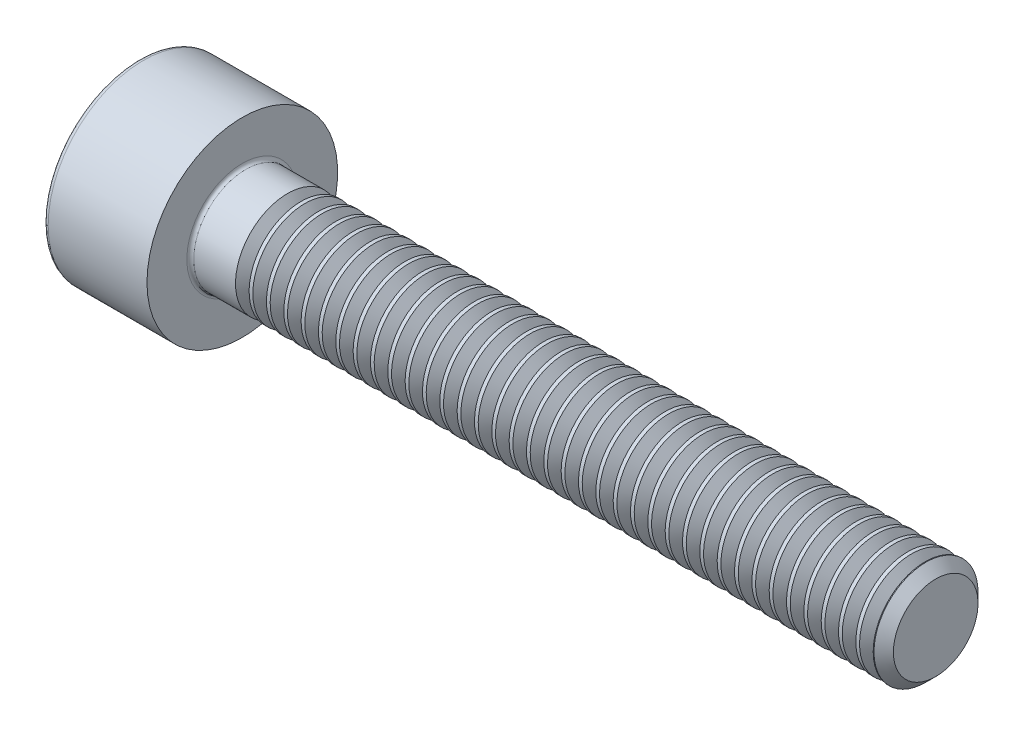
SolidWorks part; units mm, degrees
revolve "Base-Revolve" add sketch "BodySke"
sketch "BodySke" plane through (0, 0, 0) normal (0, 0, 1) x (1, 0, 0)
  line L0 (0, 0) -> (0, 2.75)
  line L1 (0, 2.75) -> (3, 2.75)
  line L2 (3, 2.75) -> (3, 1.5)
  line L3 (3, 1.5) -> (22.7195, 1.5)
  line L4 (23, 1.2195) -> (23, 0)
  line L5 (23, 0) -> (0, 0)
  line L6 (-31.75, 0) -> (127, 0) construction
  line L8 (23, 1.2195) -> (22.7195, 1.5)
  line L10 (23, -1.2195) -> (22.7195, -1.5) construction
  line L11 (3.5, 9.525) -> (3.5, 3.175) construction
  line L12 (3, 9.525) -> (3, 3.175) construction
  line L13 (-37, 9.525) -> (-37, 3.175) construction
  dimension "Head_ht" = 3
  dimension "Length" = 20
  dimension "Body_ch_ang" = 45
  dimension "Diameter" = 3
  dimension "Minor_dia" = 2.439
  dimension "Advance" = 0.5
  dimension "Thread_nom" = 20
  dimension "Thread_length" = 60
  dimension "Head_dia" = 5.5
cosmetic thread "ThreadCosmetic" [suppressed]
fillet "Fillet1" radius 0.1 1 edges at (3, 0, 1.5)
fillet "Fillet2" radius 0.15 1 edges at (0, 0, 2.75)
ref_plane "Plane1" through (0, 0, 0) normal (0, 0, 1) x (1, 0, 0)
ref_plane "Plane2" through (0, 0, 0) normal (0, 1, 0) x (1, 0, 0)
ref_plane "Plane3" through (0, 0, 0) normal (1, 0, 0) x (0, 0, -1)
other "Configuration Table"
sketch "Sketch2" plane through (0, 0, 0) normal (0, 0, 1) x (1, 0, 0)
  line L0 (0, 1.28) -> (1.3, 1.28)
  line L1 (1.3, 1.28) -> (2.039, 0)
  line L2 (-31.75, 0) -> (127, 0) construction
  line L3 (2.039, 0) -> (0, 0)
  line L4 (0, 0) -> (0, 1.28)
  line L6 (0, 0) -> (47.625, 0) construction
  dimension "D1" = 1.28
  dimension "D2" = 60
  dimension "Depth" = 1.3
revolve "Hex-PreBroach" cut sketch "Sketch2" angle 360 about L6
sketch "Sketch3" plane through (0, 0, 0) normal (-1, 0, 0) x (0, 0.5, 0.866)
  line L0 (0.739, 1.28) -> (-0.739, 1.28)
  line L1 (-0.739, 1.28) -> (-1.478, 0)
  line L2 (0.739, 1.28) -> (1.478, 0)
  line L3 (0.739, -1.28) -> (1.478, 0)
  line L4 (0.739, -1.28) -> (-0.739, -1.28)
  line L5 (-0.739, -1.28) -> (-1.478, 0)
  dimension "D1" = 1.28
  dimension "D2" = 1.28
  dimension "Hex_size" = 2.56
extrude "Hex" cut sketch "Sketch3" against normal blind 1.3
sketch "ThdSchSke" plane through (0, 0, 0) normal (0, 0, 1) x (1, 0, 0)
  line L0 (4.5, -1.2195) -> (4.3036, -1.5)
  line L1 (4.5, -1.2195) -> (4.6964, -1.5)
  line L2 (4.6964, -1.5) -> (4.6964, -1.875)
  line L3 (-3.175, 0) -> (5.1513, 0) construction
  line L4 (0, 2.6) -> (0, -2.6) construction
  line L5 (4.6964, -1.875) -> (4.3036, -1.875)
  line L6 (4.3036, -1.875) -> (4.3036, -1.5)
  dimension "Thread_minor" = 2.439
  dimension "Diameter" = 3
  dimension "Start" = 4.5
revolve "ThreadSchematic" cut sketch "ThdSchSke" angle 360 about L3
pattern_linear "ThdSchPat" count 37 spacing 0.5 along (1, 0, 0) of "ThreadSchematic"
equation "\"D2@Sketch3\" = \"Hex_size@Sketch3\" / 2"
equation "\"D1@Sketch3\" = \"Hex_size@Sketch3\" / 2"
equation "\"D1@Sketch2\" = \"Hex_size@Sketch3\" / 2"
equation "\"Thread_minor@ThreadCosmetic\"  =  \"Minor_dia@BodySke\""
equation "\"Depth@Sketch2\" =  \"Key_eng@Hex\""
equation "\"Thread_length@ThreadCosmetic\" = ((sgn( (\"Length@BodySke\" - \"Advance@BodySke\" * 3.0) - \"Thread_nom@BodySke\" )-1)*( (\"Length@BodySke\" - \"Advance@BodySke\" * 3.0) - \"Thread_nom@BodySke\" ))/-2+ \"Thread_nom@BodySke\""
equation "\"Thread_minor@ThdSchSke\" = \"Minor_dia@BodySke\""
equation "\"Diameter@ThdSchSke\" = \"Diameter@BodySke\""
equation "\"Overcut@ThdSchSke\" = \"Diameter@BodySke\" * 1.25"
equation "\"Start@ThdSchSke\" = \"Head_ht@BodySke\" + \"Length@BodySke\" - \"Thread_length@ThreadCosmetic\"  '---Non-countersunk---"
equation "\"Num_threads@ThdSchPat\" = int( \"Thread_length@ThreadCosmetic\" / \"Advance@BodySke\" + 0.999 )  + 1"
equation "\"Advance@ThdSchPat\" = \"Thread_length@ThreadCosmetic\" /  (\"Num_threads@ThdSchPat\" - 1) 'relax it"
equation "\"Num_threads@ThdSchPat\" = \"Num_threads@ThdSchPat\" - sgn( \"Num_threads@ThdSchPat\" - 1) '---chamfered tips only---"
